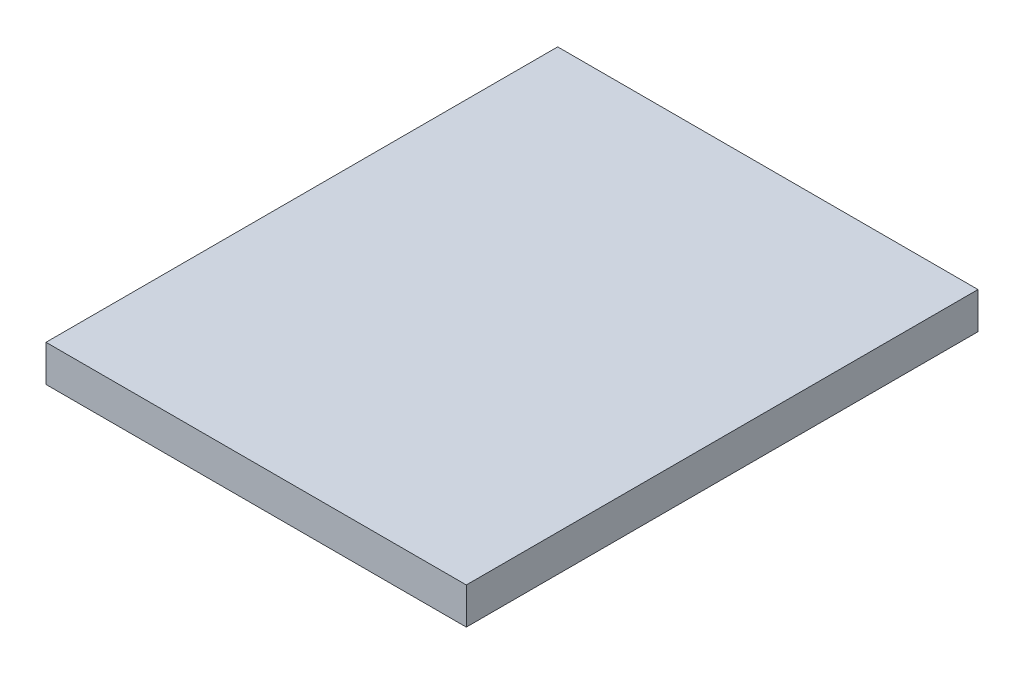
SolidWorks part; units mm, degrees
ref_plane "Front Plane" through (0, 0, 0) normal (0, 0, 1) x (1, 0, 0)
ref_plane "Top Plane" through (0, 0, 0) normal (0, 1, 0) x (1, 0, 0)
ref_plane "Right Plane" through (0, 0, 0) normal (1, 0, 0) x (0, 0, -1)
sketch "Sketch1" plane through (0, 0, 0) normal (0, 1, 0) x (1, 0, 0)
  line L1 (0, 0) -> (230, 0)
  line L2 (0, 0) -> (0, 280)
  line L3 (0, 280) -> (230, 280)
  line L4 (230, 0) -> (230, 280)
  dimension "D1" = 230
  dimension "D2" = 280
extrude "Boss-Extrude1" add sketch "Sketch1" along normal blind 20
sketch "Sketch2" plane through (0, 0, 0) normal (0, 1, 0) x (1, 0, 0)
  line L0 (0, 280) -> (0, 0) construction
  line L1 (214.705, 263.5) -> (15.295, 263.5)
  line L2 (214.705, 263.5) -> (214.705, 16.5)
  line L3 (214.705, 16.5) -> (15.295, 16.5)
  line L4 (15.295, 263.5) -> (15.295, 16.5)
  line L5 (230, 280) -> (0, 280) construction
  point P4 (15.295, 140)
  point P7 (0, 140)
  point P8 (115, 263.5)
  point P11 (115, 280)
  dimension "D1" = 199.41
  dimension "D2" = 247
extrude "Boss-Extrude2" add sketch "Sketch2" against normal blind 10
